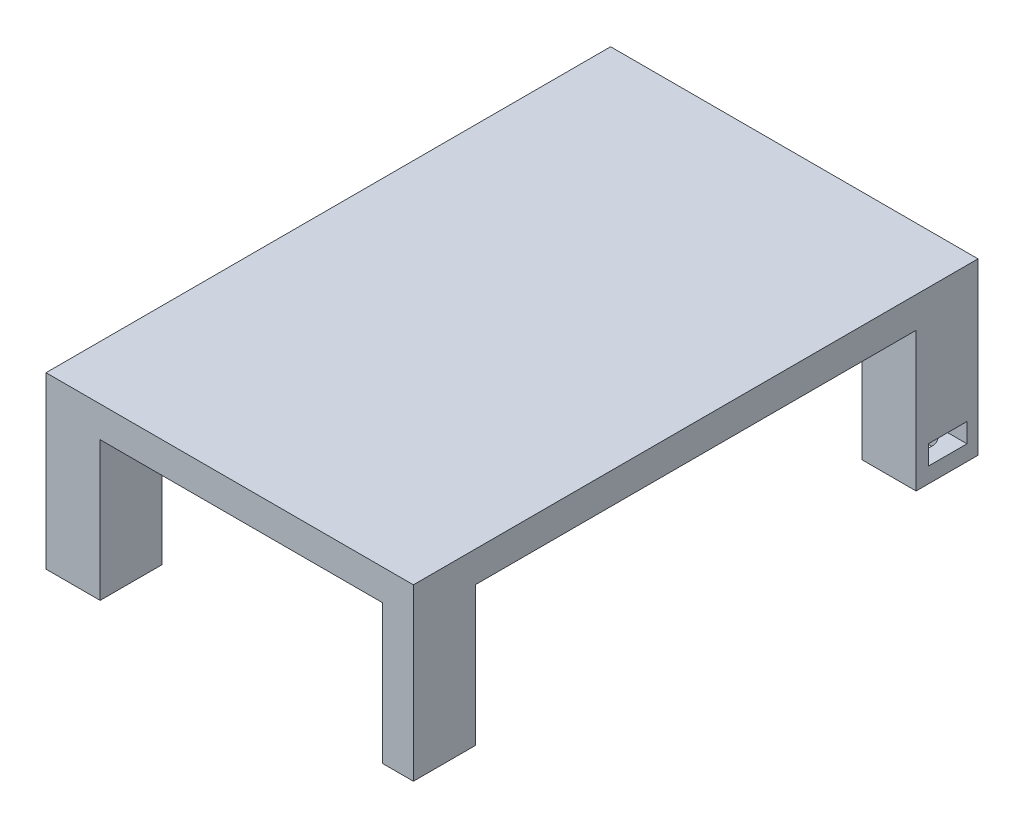
SolidWorks part; units mm, degrees
ref_plane "Front Plane" through (0, 0, 0) normal (0, 0, 1) x (1, 0, 0)
ref_plane "Top Plane" through (0, 0, 0) normal (0, 1, 0) x (1, 0, 0)
ref_plane "Right Plane" through (0, 0, 0) normal (1, 0, 0) x (0, 0, -1)
sketch "Sketch1" plane through (0, 0, 0) normal (0, 1, 0) x (1, 0, 0)
  line L1 (-57.3745, 37.3181) -> (-9.8745, 37.3181)
  line L2 (-57.3745, 37.3181) -> (-57.3745, -35.6819)
  line L3 (-57.3745, -35.6819) -> (-9.8745, -35.6819)
  line L4 (-9.8745, 37.3181) -> (-9.8745, -35.6819)
  dimension "D1" = 47.5
  dimension "D2" = 73
extrude "Boss-Extrude1" add sketch "Sketch1" along normal blind 22 contours L1 L4 L3 L2
sketch "Sketch2" plane through (0, 0, 0) normal (0, -1, 0) x (1, 0, 0)
  line L0 (-57.3745, 27.6819) -> (-50.3745, 27.6819)
  line L1 (-57.3745, -37.3181) -> (-57.3745, 35.6819) construction
  line L2 (-50.3745, 27.6819) -> (-50.3745, 35.6819)
  line L3 (-57.3745, 35.6819) -> (-9.8745, 35.6819) construction
  line L4 (-9.8745, -29.3181) -> (-16.8745, -29.3181)
  line L5 (-9.8745, -37.3181) -> (-9.8745, 35.6819) construction
  line L6 (-16.8745, -29.3181) -> (-16.8745, -37.3181)
  line L7 (-57.3745, -37.3181) -> (-9.8745, -37.3181) construction
  line L8 (-57.3745, -37.3181) -> (-53.3745, -37.3181)
  line L9 (-53.3745, -37.3181) -> (-53.3745, -29.3181)
  line L10 (-53.3745, -29.3181) -> (-57.3745, -29.3181)
  line L11 (-13.8745, 35.6819) -> (-13.8745, 27.6819)
  line L12 (-13.8745, 27.6819) -> (-9.8745, 27.6819)
  line L13 (-50.3745, 35.6819) -> (-13.8745, 35.6819)
  line L14 (-9.8745, -29.3181) -> (-9.8745, 27.6819)
  line L15 (-57.3745, -29.3181) -> (-57.3745, 27.6819)
  line L16 (-16.8745, -37.3181) -> (-53.3745, -37.3181)
  dimension "D1" = 7
  dimension "D2" = 8
  dimension "D3" = 8
  dimension "D4" = 7
  dimension "D5" = 4
  dimension "D6" = 8
  dimension "D7" = 4
  dimension "D8" = 8
extrude "Cut-Extrude1" cut sketch "Sketch2" against normal blind 18 contours L9 L10 L15 L0 L2 L13 L11 L12 L14 L4 L6 L16
sketch "Sketch4" plane through (0, 0, 0) normal (0, -1, 0) x (1, 0, 0)
  circle A0 centre (-53.3745, 31.6819) radius 2
  circle A1 centre (-13.8745, -33.3181) radius 2
extrude "Cut-Extrude2" cut sketch "Sketch4" against normal blind 18
sketch "Sketch5" plane through (-57.3745, 0, 0) normal (-1, 0, 0) x (0, 0, 1)
  line L1 (29.2986, 4.5) -> (34.2986, 4.5)
  line L2 (29.2986, 4.5) -> (29.2986, 2)
  line L3 (29.2986, 2) -> (34.2986, 2)
  line L4 (34.2986, 4.5) -> (34.2986, 2)
extrude "Cut-Extrude3" cut sketch "Sketch5" against normal blind 6.5 contours L3 L4 L1 L2
sketch "Sketch9" plane through (-9.8745, 0, 0) normal (1, 0, 0) x (0, 0, -1)
  line L1 (30.8947, 4.5) -> (35.8947, 4.5)
  line L2 (30.8947, 4.5) -> (30.8947, 2)
  line L3 (30.8947, 2) -> (35.8947, 2)
  line L4 (35.8947, 4.5) -> (35.8947, 2)
extrude "Cut-Extrude4" cut sketch "Sketch9" against normal blind 6.5 contours L3 L4 L1 L2
